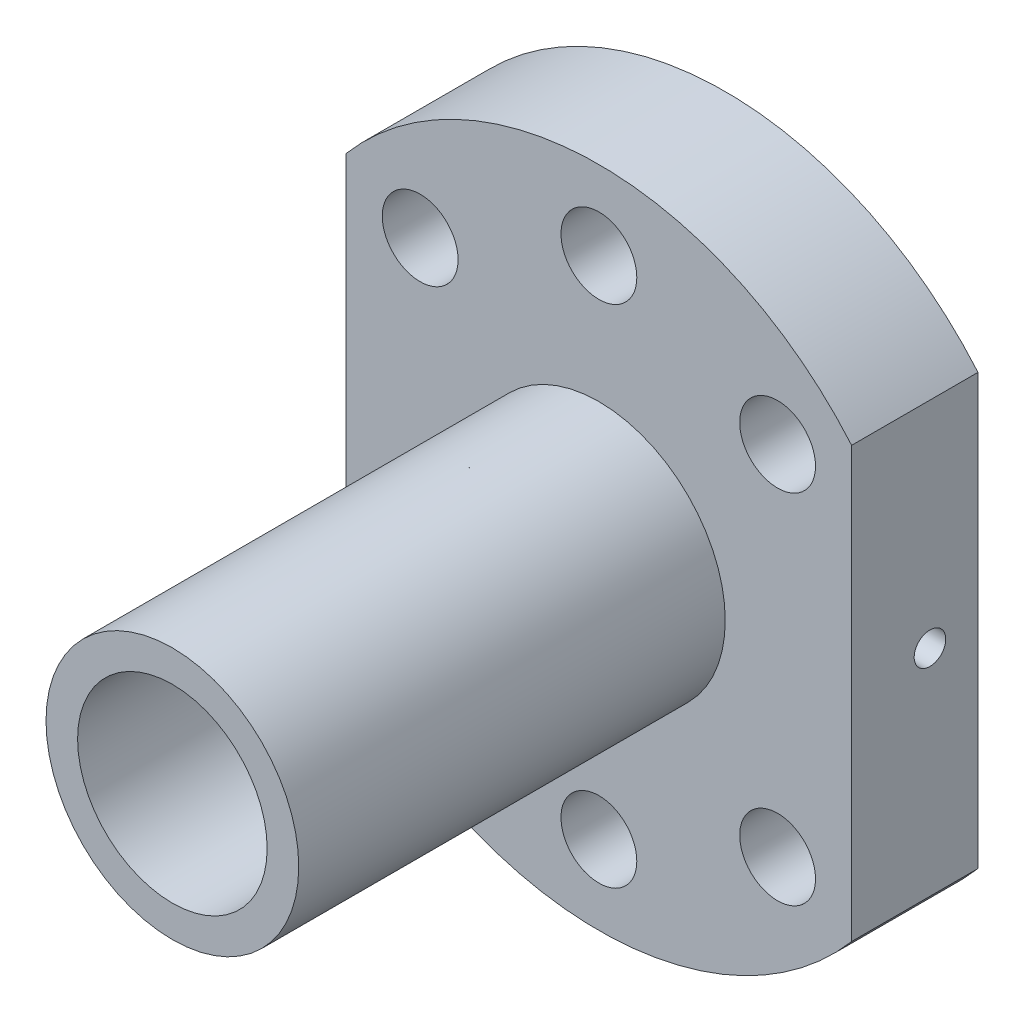
SolidWorks part; units mm, degrees
ref_plane "前视基准面" through (0, 0, 0) normal (0, 0, 1) x (1, 0, 0)
ref_plane "上视基准面" through (0, 0, 0) normal (0, 1, 0) x (1, 0, 0)
ref_plane "右视基准面" through (0, 0, 0) normal (1, 0, 0) x (0, 0, -1)
sketch "草图2" plane through (0, 0, 0) normal (0, 0, 1) x (1, 0, 0)
  line L0 (-798.1609, 0) -> (39109.8844, 0) construction
  line L1 (0, -798.1609) -> (0, 39109.8844) construction
  line L2 (-16, 13.6015) -> (-16, -13.6015)
  line L3 (16, -13.6015) -> (16, 13.6015)
  line L4 (-16, 13.6015) -> (16, 13.6015) construction
  line L5 (-16, 21) -> (17.2551, 21) construction
  line L6 (-14.2569, -21) -> (17.2551, -21) construction
  arc A0 (-16, -13.6015) -> (16, -13.6015) centre (0, 0) ccw
  arc A1 (16, 13.6015) -> (-16, 13.6015) centre (0, 0) ccw
  dimension "D3" = 42
  dimension "D4" = 21
  dimension "D1" = 16
  dimension "D2" = 32
extrude "凸台-拉伸1" add sketch "草图2" along normal blind 8
sketch "草图3" plane through (0, 0, 8) normal (0, 0, 1) x (1, 0, 0)
  circle A0 centre (0, 0) radius 6
  circle A1 centre (0, 0) radius 8
  dimension "D1" = 12
  dimension "D2" = 2
extrude "凸台-拉伸3" add sketch "草图3" along normal blind 27
sketch "草图5" plane through (0, 0, 8) normal (0, 0, 1) x (1, 0, 0)
  circle A0 centre (0, 0) radius 6
extrude "切除-拉伸1" cut sketch "草图5" against normal through all
sketch "草图6" plane through (0, 0, 8) normal (0, 0, 1) x (1, 0, 0)
  line L0 (0, -1000) -> (0, 49000) construction
  circle A0 centre (0, 0) radius 16 construction
  circle A1 centre (0, 16) radius 2.4
  circle A2 centre (11.3137, 11.3137) radius 2.4
  circle A4 centre (11.3137, -11.3137) radius 2.4
  circle A5 centre (0, -16) radius 2.4
  circle A6 centre (-11.3137, -11.3137) radius 2.4
  circle A8 centre (-11.3137, 11.3137) radius 2.4
  circle A19 centre (-16, 0) radius 2.4 [skipped]
  circle A20 centre (16, 0) radius 2.4 [skipped]
  point P24 (0, 0)
  point P25 (0, 0)
  dimension "D1" = 8
extrude "切除-拉伸2" cut sketch "草图6" against normal through all
sketch "草图7" plane through (0, 0, 0) normal (0, 0, -1) x (-1, 0, 0)
  circle A0 centre (0, 0) radius 9
extrude "切除-拉伸3" cut sketch "草图7" against normal blind 1.5
sketch "草图8" plane through (-16, 0, 0) normal (-1, 0, 0) x (0, 0, 1)
  circle A0 centre (3.0409, 0) radius 1
extrude "切除-拉伸4" cut sketch "草图8" against normal through all
